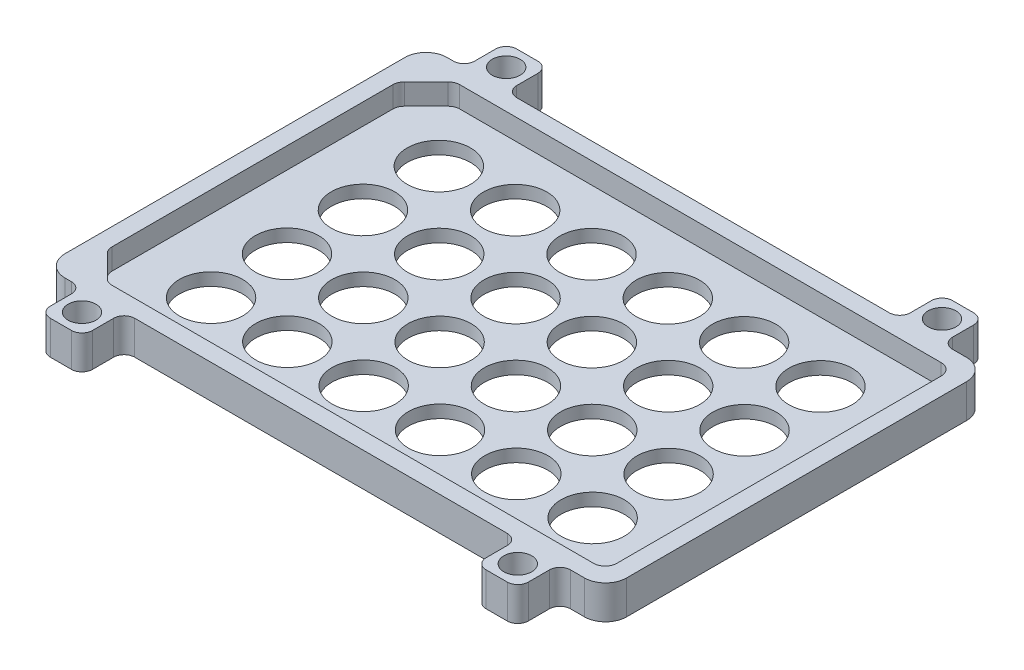
SolidWorks part; units mm, degrees
ref_plane "Front Plane" through (0, 0, 0) normal (0, 0, 1) x (1, 0, 0)
ref_plane "Top Plane" through (0, 0, 0) normal (0, 1, 0) x (1, 0, 0)
ref_plane "Right Plane" through (0, 0, 0) normal (1, 0, 0) x (0, 0, -1)
sketch "Sketch1" plane through (0, 0, 0) normal (0, 1, 0) x (1, 0, 0)
  line L1 (0, 0) -> (157.864, 0)
  line L2 (0, 0) -> (0, -90.551)
  line L3 (0, -90.551) -> (157.864, -90.551)
  line L4 (157.864, 0) -> (157.864, -90.551)
  dimension "D1" = 157.864
  dimension "D2" = 90.551
extrude "Boss-Extrude1" add sketch "Sketch1" along normal blind 8
sketch "Sketch7" plane through (0, 0, 0) normal (0, -1, 0) x (1, 0, 0)
  circle A0 centre (33.602, 72.2755) radius 8.95
  circle A1 centre (33.602, 18.2755) radius 8.5
  circle A2 centre (51.692, 72.2755) radius 8.95
  circle A3 centre (69.782, 72.2755) radius 8.95
  circle A4 centre (87.872, 72.2755) radius 8.95
  circle A5 centre (105.962, 72.2755) radius 8.95
  circle A6 centre (124.052, 72.2755) radius 8.95
  circle A7 centre (51.692, 54.2755) radius 8.95
  circle A8 centre (69.782, 54.2755) radius 8.95
  circle A9 centre (87.872, 54.2755) radius 8.95
  circle A10 centre (105.962, 54.2755) radius 8.95
  circle A11 centre (124.052, 54.2755) radius 8.95
  circle A12 centre (51.692, 36.2755) radius 8.95
  circle A13 centre (69.782, 36.2755) radius 8.95
  circle A14 centre (87.872, 36.2755) radius 8.95
  circle A15 centre (105.962, 36.2755) radius 8.95
  circle A16 centre (124.052, 36.2755) radius 8.95
  circle A17 centre (51.692, 18.2755) radius 8.95
  circle A18 centre (69.782, 18.2755) radius 8.95
  circle A19 centre (87.872, 18.2755) radius 8.95
  circle A20 centre (105.962, 18.2755) radius 8.95
  circle A21 centre (124.052, 18.2755) radius 8.95
  circle A22 centre (33.602, 54.2755) radius 8.95
  circle A23 centre (33.602, 36.2755) radius 8.95
  circle A24 centre (33.602, 18.2755) radius 8.95
  circle A25 centre (51.692, 18.2755) radius 8.5
  circle A26 centre (69.782, 18.2755) radius 8.5
  circle A27 centre (87.872, 18.2755) radius 8.5
  circle A28 centre (105.962, 18.2755) radius 8.5
  circle A29 centre (124.052, 18.2755) radius 8.5
  circle A30 centre (33.602, 36.2755) radius 8.5
  circle A31 centre (51.692, 36.2755) radius 8.5
  circle A32 centre (69.782, 36.2755) radius 8.5
  circle A33 centre (87.872, 36.2755) radius 8.5
  circle A34 centre (105.962, 36.2755) radius 8.5
  circle A35 centre (124.052, 36.2755) radius 8.5
  circle A36 centre (33.602, 54.2755) radius 8.5
  circle A37 centre (51.692, 54.2755) radius 8.5
  circle A38 centre (69.782, 54.2755) radius 8.5
  circle A39 centre (87.872, 54.2755) radius 8.5
  circle A40 centre (105.962, 54.2755) radius 8.5
  circle A41 centre (124.052, 54.2755) radius 8.5
  circle A42 centre (124.052, 72.2755) radius 8.5
  circle A43 centre (105.962, 72.2755) radius 8.5
  circle A44 centre (87.872, 72.2755) radius 8.5
  circle A45 centre (69.782, 72.2755) radius 8.5
  circle A46 centre (51.692, 72.2755) radius 8.5
  circle A47 centre (33.602, 72.2755) radius 8.5
  dimension "D1" = 17.9
  dimension "D2" = 17
  dimension "D6" = 18
  dimension "D3" = 18.09
  dimension "D4" = 18
  dimension "D5" = 18.09
  dimension "D7" = 6
  dimension "D8" = 4
sketch "Sketch23" plane through (0, 8, 0) normal (0, 1, 0) x (1, 0, 0)
  line L1 (141.332, -86.4755) -> (23.3181, -86.4755)
  line L2 (141.332, -86.4755) -> (141.332, -4.0755)
  line L3 (141.332, -4.0755) -> (23.3181, -4.0755)
  line L4 (16.532, -79.6894) -> (16.532, -10.8616)
  line L5 (16.532, -10.8616) -> (23.3181, -4.0755)
  line L6 (23.3181, -4.0755) -> (16.532, -4.0755) construction
  line L7 (16.532, -4.0755) -> (16.532, -10.8616) construction
  line L8 (23.3181, -86.4755) -> (16.532, -79.6894)
  line L10 (157.864, 0) -> (0, 0) construction
  line L11 (141.332, -4.0755) -> (141.332, 0) construction
  line L12 (23.3181, -86.4755) -> (16.532, -86.4755) construction
  line L13 (16.532, -86.4755) -> (16.532, -79.6894) construction
  line L14 (157.864, -90.551) -> (157.864, 0) construction
  line L15 (141.332, -86.4755) -> (157.864, -86.4755) construction
  line L16 (16.532, -86.4755) -> (0, -86.4755) construction
  line L17 (0, 0) -> (0, -90.551) construction
  line L18 (157.864, 0) -> (0, 0) construction
  line L19 (141.332, -86.4755) -> (141.332, -90.551) construction
  line L20 (0, -90.551) -> (157.864, -90.551) construction
  dimension "D2" = 124.8
  dimension "D3" = 9.597
  dimension "D5" = 9.597
  dimension "D9" = 82.4
  dimension "D10" = 4.0755
extrude "Cut-Extrude21" cut sketch "Sketch23" against normal blind 5
fillet "Fillet8" radius 2.75 6 edges at (141.332, 5.5, 4.0755) (16.532, 5.5, 10.8616) (23.3181, 5.5, 4.0755) (141.332, 5.5, 86.4755) (23.3181, 5.5, 86.4755) (16.532, 5.5, 79.6894)
sketch "Sketch29" plane through (0, 8, 0) normal (0, 1, 0) x (1, 0, 0)
  line L0 (157.864, 0) -> (0, 0) construction
  line L1 (157.864, -90.551) -> (145.4887, -90.551)
  line L2 (157.864, -90.551) -> (157.864, 0)
  line L3 (157.864, 0) -> (145.4887, 0)
  line L4 (145.4887, -90.551) -> (145.4887, 0)
  line L6 (0, -90.551) -> (12.3753, -90.551)
  line L7 (0, -90.551) -> (0, 0)
  line L8 (0, 0) -> (12.3753, 0)
  line L9 (12.3753, -90.551) -> (12.3753, 0)
  dimension "D2" = 4.0755
extrude "Cut-Extrude25" cut sketch "Sketch29" against normal through all
fillet "Fillet9" radius 5 4 edges at (145.4887, 4, 90.551) (145.4887, 4, 0) (12.3753, 4, 90.551) (12.3753, 4, 0)
sketch "Sketch36" plane through (0, 0, 0) normal (0, -1, 0) x (1, 0, 0)
  line L0 (17.3753, 90.551) -> (140.4887, 90.551) construction
  line L1 (21.3936, 90.551) -> (31.3936, 90.551)
  line L2 (21.3936, 90.551) -> (21.3936, 100.551)
  line L3 (21.3936, 100.551) -> (31.3936, 100.551)
  line L4 (31.3936, 90.551) -> (31.3936, 100.551)
  line L5 (140.4887, 0) -> (17.3753, 0) construction
  line L6 (124.6936, 90.551) -> (134.6936, 90.551)
  line L7 (124.6936, 90.551) -> (124.6936, 100.551)
  line L8 (124.6936, 100.551) -> (134.6936, 100.551)
  line L9 (134.6936, 90.551) -> (134.6936, 100.551)
  line L10 (31.3936, 0) -> (21.3936, 0)
  line L11 (31.3936, 0) -> (31.3936, -10)
  line L12 (31.3936, -10) -> (21.3936, -10)
  line L13 (21.3936, 0) -> (21.3936, -10)
  line L15 (124.6936, 0) -> (134.6936, 0)
  line L16 (124.6936, 0) -> (124.6936, -10)
  line L17 (124.6936, -10) -> (134.6936, -10)
  line L18 (134.6936, 0) -> (134.6936, -10)
  line L22 (134.6936, 90.551) -> (124.6936, 100.551) construction
  line L23 (124.6936, 90.551) -> (134.6936, 100.551) construction
  line L24 (31.3936, 100.551) -> (21.3936, 90.551) construction
  line L25 (31.3936, 90.551) -> (21.3936, 100.551) construction
  line L26 (21.3936, 0) -> (31.3936, -10) construction
  line L27 (31.3936, 0) -> (21.3936, -10) construction
  line L28 (21.3936, -10) -> (21.4692, -10.0262) construction
  line L29 (134.6936, 0) -> (124.6936, -10) construction
  line L30 (134.6936, -10) -> (124.6936, 0) construction
  circle A0 centre (129.6936, -5) radius 3.3
  circle A1 centre (26.3936, -5) radius 3.3
  circle A2 centre (26.3936, 95.551) radius 3.3
  circle A3 centre (129.6936, 95.551) radius 3.3
  dimension "D5" = 6.6
  dimension "D9" = 6.6
  dimension "D10" = 5.7951
  dimension "D1" = 93.3
  dimension "D2" = 93.3
  dimension "D3" = 10
  dimension "D4" = 10
  dimension "D6" = 4.0183
  dimension "D7" = 4.0183
  dimension "D8" = 5.7951
extrude "Boss-Extrude10" add sketch "Sketch36" against normal up to surface (8 mm away) up to face at (78.932, 8, 45.2755)
fillet "Fillet10" radius 2.5 16 edges at (21.3936, 4, 100.551) (31.3936, 4, 100.551) (124.6936, 4, 100.551) (134.6936, 4, 100.551) (134.6936, 4, -10) (124.6936, 4, -10) (31.3936, 4, -10) (21.3936, 4, -10) (124.6936, 4, 90.551) (21.3936, 4, 90.551) (134.6936, 4, 90.551) (31.3936, 4, 90.551) (134.6936, 4, 0) (124.6936, 4, 0) (31.3936, 4, 0) (21.3936, 4, 0)
sketch "Sketch37" plane through (0, 3, 0) normal (0, 1, 0) x (1, 0, 0)
  line L0 (124.157, -72.2755) -> (124.157, -86.4755) construction
  line L1 (124.157, -72.2755) -> (141.332, -72.2755) construction
  line L2 (141.332, -83.7255) -> (141.332, -6.8255) construction
  line L3 (33.707, -18.2755) -> (33.707, -4.0755) construction
  line L4 (138.582, -4.0755) -> (24.4572, -4.0755) construction
  line L5 (33.707, -18.2755) -> (16.532, -18.2755) construction
  line L6 (16.532, -12.0007) -> (16.532, -78.5503) construction
  line L7 (24.4572, -86.4755) -> (138.582, -86.4755) construction
  circle A0 centre (124.157, -72.2755) radius 7.5
  circle A1 centre (106.067, -72.2755) radius 7.5
  circle A2 centre (87.977, -72.2755) radius 7.5
  circle A3 centre (69.887, -72.2755) radius 7.5
  circle A4 centre (51.797, -72.2755) radius 7.5
  circle A5 centre (33.707, -72.2755) radius 7.5
  circle A6 centre (106.067, -54.2755) radius 7.5
  circle A7 centre (87.977, -54.2755) radius 7.5
  circle A8 centre (69.887, -54.2755) radius 7.5
  circle A9 centre (51.797, -54.2755) radius 7.5
  circle A10 centre (33.707, -54.2755) radius 7.5
  circle A11 centre (106.067, -36.2755) radius 7.5
  circle A12 centre (87.977, -36.2755) radius 7.5
  circle A13 centre (69.887, -36.2755) radius 7.5
  circle A14 centre (51.797, -36.2755) radius 7.5
  circle A15 centre (33.707, -36.2755) radius 7.5
  circle A16 centre (106.067, -18.2755) radius 7.5
  circle A17 centre (87.977, -18.2755) radius 7.5
  circle A18 centre (69.887, -18.2755) radius 7.5
  circle A19 centre (51.797, -18.2755) radius 7.5
  circle A20 centre (33.707, -18.2755) radius 7.5
  circle A21 centre (124.157, -54.2755) radius 7.5
  circle A22 centre (124.157, -36.2755) radius 7.5
  circle A23 centre (124.157, -18.2755) radius 7.5
  dimension "D1" = 15
extrude "Cut-Extrude26" cut sketch "Sketch37" against normal up to surface (3 mm away) up to face at (78.2213, 0, 45.2755)
